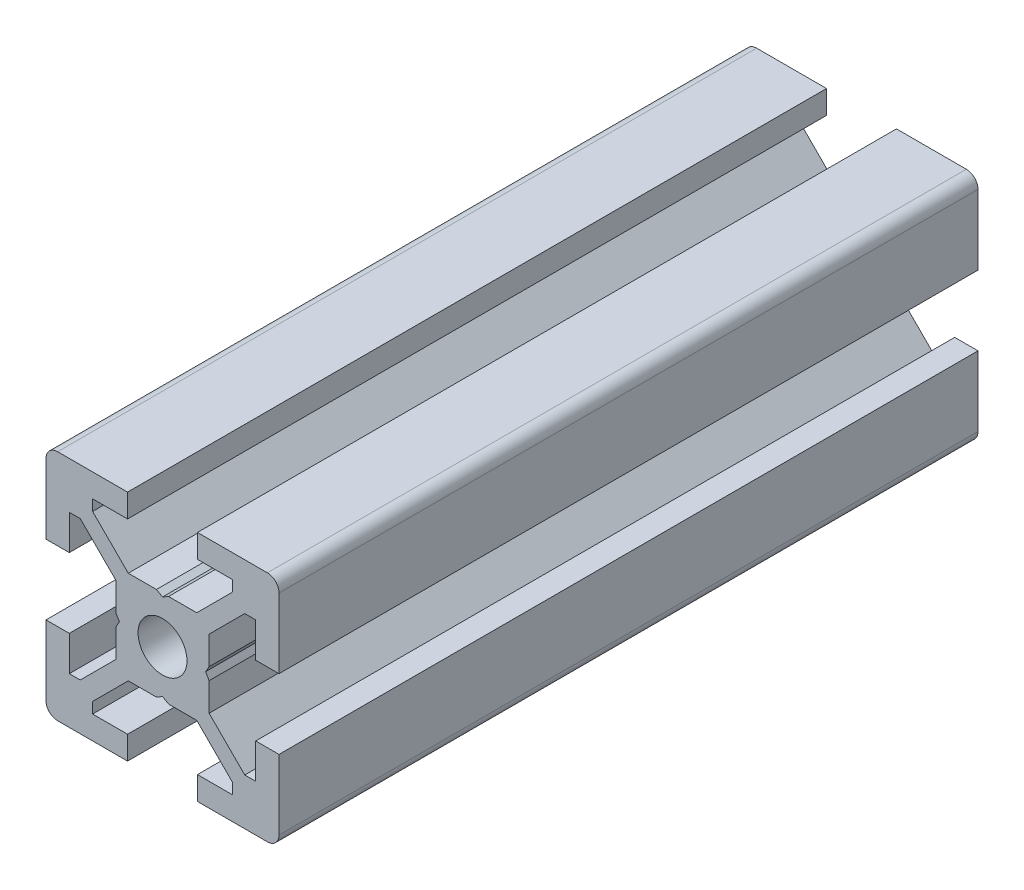
SolidWorks part; units mm, degrees
ref_plane "Front Plane" through (0, 0, 0) normal (0, 0, 1) x (1, 0, 0)
ref_plane "Top Plane" through (0, 0, 0) normal (0, 1, 0) x (1, 0, 0)
ref_plane "Right Plane" through (0, 0, 0) normal (1, 0, 0) x (0, 0, -1)
ref_plane "Plane1" through (0, 0, 0) normal (0, 0, 1) x (1, 0, 0)
sketch "Sketch1" plane through (0, 0, 0) normal (0, 0, 1) x (1, 0, 0)
  line L0 (-10, -3) -> (-10, -9)
  line L1 (-9, -10) -> (-3, -10)
  line L2 (-3, -10) -> (-3, -8)
  line L3 (-3, -8) -> (-6, -8)
  line L4 (-6, -8) -> (-6, -7.0607)
  line L5 (-6, -7.0607) -> (-2.9393, -4)
  line L6 (-2.9393, -4) -> (-0.5196, -4)
  line L7 (-0.5196, -4) -> (0, -3.7)
  line L8 (0, -3.7) -> (0.5196, -4)
  line L9 (0.5196, -4) -> (2.9393, -4)
  line L10 (2.9393, -4) -> (6, -7.0607)
  line L11 (6, -7.0607) -> (6, -8)
  line L12 (6, -8) -> (3, -8)
  line L13 (3, -8) -> (3, -10)
  line L14 (3, -10) -> (9, -10)
  line L15 (10, -9) -> (10, -3)
  line L16 (10, -3) -> (8, -3)
  line L17 (8, -3) -> (8, -6)
  line L18 (8, -6) -> (7.0607, -6)
  line L19 (7.0607, -6) -> (4, -2.9393)
  line L20 (4, -2.9393) -> (4, -0.5196)
  line L21 (4, -0.5196) -> (3.7, 0)
  line L22 (3.7, 0) -> (4, 0.5196)
  line L23 (4, 0.5196) -> (4, 2.9393)
  line L24 (4, 2.9393) -> (7.0607, 6)
  line L25 (7.0607, 6) -> (8, 6)
  line L26 (8, 6) -> (8, 3)
  line L27 (8, 3) -> (10, 3)
  line L28 (10, 3) -> (10, 9)
  line L29 (9, 10) -> (3, 10)
  line L30 (3, 10) -> (3, 8)
  line L31 (3, 8) -> (6, 8)
  line L32 (6, 8) -> (6, 7.0607)
  line L33 (6, 7.0607) -> (2.9393, 4)
  line L34 (2.9393, 4) -> (0.5196, 4)
  line L35 (0.5196, 4) -> (0, 3.7)
  line L36 (0, 3.7) -> (-0.5196, 4)
  line L37 (-0.5196, 4) -> (-2.9393, 4)
  line L38 (-2.9393, 4) -> (-6, 7.0607)
  line L39 (-6, 7.0607) -> (-6, 8)
  line L40 (-6, 8) -> (-3, 8)
  line L41 (-3, 8) -> (-3, 10)
  line L42 (-3, 10) -> (-9, 10)
  line L43 (-10, 9) -> (-10, 3)
  line L44 (-10, 3) -> (-8, 3)
  line L45 (-8, 3) -> (-8, 6)
  line L46 (-8, 6) -> (-7.0607, 6)
  line L47 (-7.0607, 6) -> (-4, 2.9393)
  line L48 (-4, 2.9393) -> (-4, 0.5196)
  line L49 (-4, 0.5196) -> (-3.7, 0)
  line L50 (-3.7, 0) -> (-4, -0.5196)
  line L51 (-4, -0.5196) -> (-4, -2.9393)
  line L52 (-4, -2.9393) -> (-7.0607, -6)
  line L53 (-7.0607, -6) -> (-8, -6)
  line L54 (-8, -6) -> (-8, -3)
  line L55 (-8, -3) -> (-10, -3)
  arc A0 (-10, -9) -> (-9, -10) centre (-9, -9) ccw
  arc A1 (9, -10) -> (10, -9) centre (9, -9) ccw
  arc A2 (10, 9) -> (9, 10) centre (9, 9) ccw
  arc A3 (-9, 10) -> (-10, 9) centre (-9, 9) ccw
extrude "Boss-Extrude1" add sketch "Sketch1" against normal blind 60
ref_plane "Plane2" through (0, 0, 0) normal (1, 0, 0) x (0, 0, -1)
sketch "Sketch2" plane through (0, 0, 0) normal (1, 0, 0) x (0, 0, -1)
  line L0 (0, 0) -> (0, 2.1)
  line L1 (0, 2.1) -> (60, 2.1)
  line L2 (60, 2.1) -> (60, 0)
  line L3 (60, 0) -> (0, 0)
  line L4 (60, 0) -> (0, 0) construction
revolve "Cut-Revolve1" cut sketch "Sketch2" angle 360 about L4
